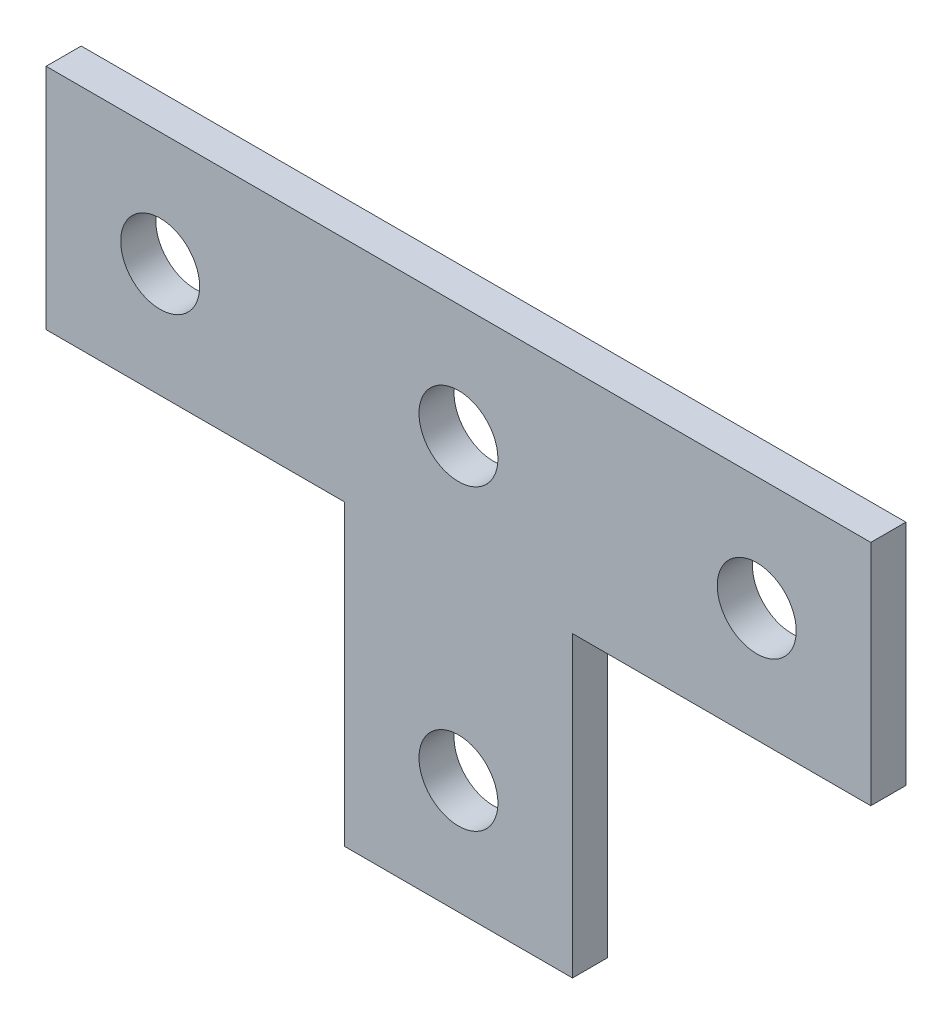
SolidWorks part; units mm, degrees
other "Markup1"
sketch "Sketch4" plane through (37.3063, -23.8125, 1.5875) normal (0.8944, -0.0077, 0.4472) x (0.2221, 0.8755, -0.4291)
ref_plane "Front Plane" through (0, 0, 0) normal (0, 0, 1) x (1, 0, 0)
ref_plane "Top Plane" through (0, 0, 0) normal (0, 1, 0) x (1, 0, 0)
ref_plane "Right Plane" through (0, 0, 0) normal (1, 0, 0) x (0, 0, -1)
sketch "Sketch1" plane through (0, 0, 0) normal (0, 0, 1) x (1, 0, 0)
  line L0 (-37.3062, 23.8125) -> (-37.3062, 3.175)
  line L1 (-37.3062, 3.175) -> (-10.3187, 3.175)
  line L2 (-10.3187, 3.175) -> (-10.3187, -23.8125)
  line L3 (-10.3187, -23.8125) -> (10.3187, -23.8125)
  line L4 (10.3187, -23.8125) -> (10.3187, 3.175)
  line L5 (10.3187, 3.175) -> (37.3063, 3.175)
  line L6 (37.3063, 3.175) -> (37.3063, 23.8125)
  line L7 (37.3063, 23.8125) -> (-37.3062, 23.8125)
  line L8 (0, -23.8125) -> (0, 23.8125) construction
  line L9 (-37.3062, 13.4937) -> (37.3062, 13.4937) construction
  circle A0 centre (0, 13.4937) radius 3.5719
  circle A1 centre (-26.9875, 13.4937) radius 3.5719
  circle A2 centre (26.9875, 13.4937) radius 3.5719
  circle A3 centre (0, -13.4938) radius 3.5719
  circle A4 centre (0, 13.4937) radius 26.9875 construction
  point P22 (0, 0)
  dimension "Hole Diameter" = 7.1437
  dimension "Length B" = 47.625
  dimension "Length A" = 74.6125
  dimension "For Strut Channel Width" = 20.6375
  dimension "Hole to Hole Spacing" = 26.9875
sketch "Sketch2" plane through (0, 0, 0) normal (1, 0, 0) x (0, 0, -1)
  line L0 (1.5875, 0) -> (-1.5875, 0) construction
  point P4 (0, 0)
  dimension "Thickness" = 3.175
sketch "Sketch3" plane through (0, 0, 0) normal (0, 0, 1) x (1, 0, 0)
  line L0 (-10.3187, -23.8125) -> (10.3187, -23.8125) construction
  line L1 (-10.3187, 3.175) -> (-10.3187, -23.8125) construction
  line L2 (-37.3062, 3.175) -> (-10.3187, 3.175) construction
  line L3 (-37.3062, 23.8125) -> (-37.3062, 3.175) construction
  line L4 (37.3063, 23.8125) -> (-37.3062, 23.8125) construction
  line L5 (37.3063, 3.175) -> (37.3063, 23.8125) construction
  line L6 (10.3187, 3.175) -> (37.3063, 3.175) construction
  line L7 (10.3187, -23.8125) -> (10.3187, 3.175) construction
  line L8 (-10.3187, -23.8125) -> (10.3187, -23.8125)
  line L9 (-10.3187, 3.175) -> (-10.3187, -23.8125)
  line L10 (-37.3062, 3.175) -> (-10.3187, 3.175)
  line L11 (-37.3062, 23.8125) -> (-37.3062, 3.175)
  line L12 (37.3063, 23.8125) -> (-37.3062, 23.8125)
  line L13 (37.3063, 3.175) -> (37.3063, 23.8125)
  line L14 (10.3187, 3.175) -> (37.3063, 3.175)
  line L15 (10.3187, -23.8125) -> (10.3187, 3.175)
  circle A0 centre (26.9875, 13.4937) radius 3.5719 construction
  circle A1 centre (0, -13.4938) radius 3.5719 construction
  circle A2 centre (-26.9875, 13.4937) radius 3.5719 construction
  circle A3 centre (0, 13.4937) radius 3.5719 construction
  circle A4 centre (26.9875, 13.4937) radius 3.5719
  circle A5 centre (0, -13.4938) radius 3.5719
  circle A6 centre (-26.9875, 13.4937) radius 3.5719
  circle A7 centre (0, 13.4937) radius 3.5719
extrude "Boss-Extrude1" add sketch "Sketch3" against normal up to vertex (1.5875 mm away) and the other way up to vertex (1.5875 mm away) up to point (0, 0, -1.5875) other way up to point (0, 0, 1.5875)
